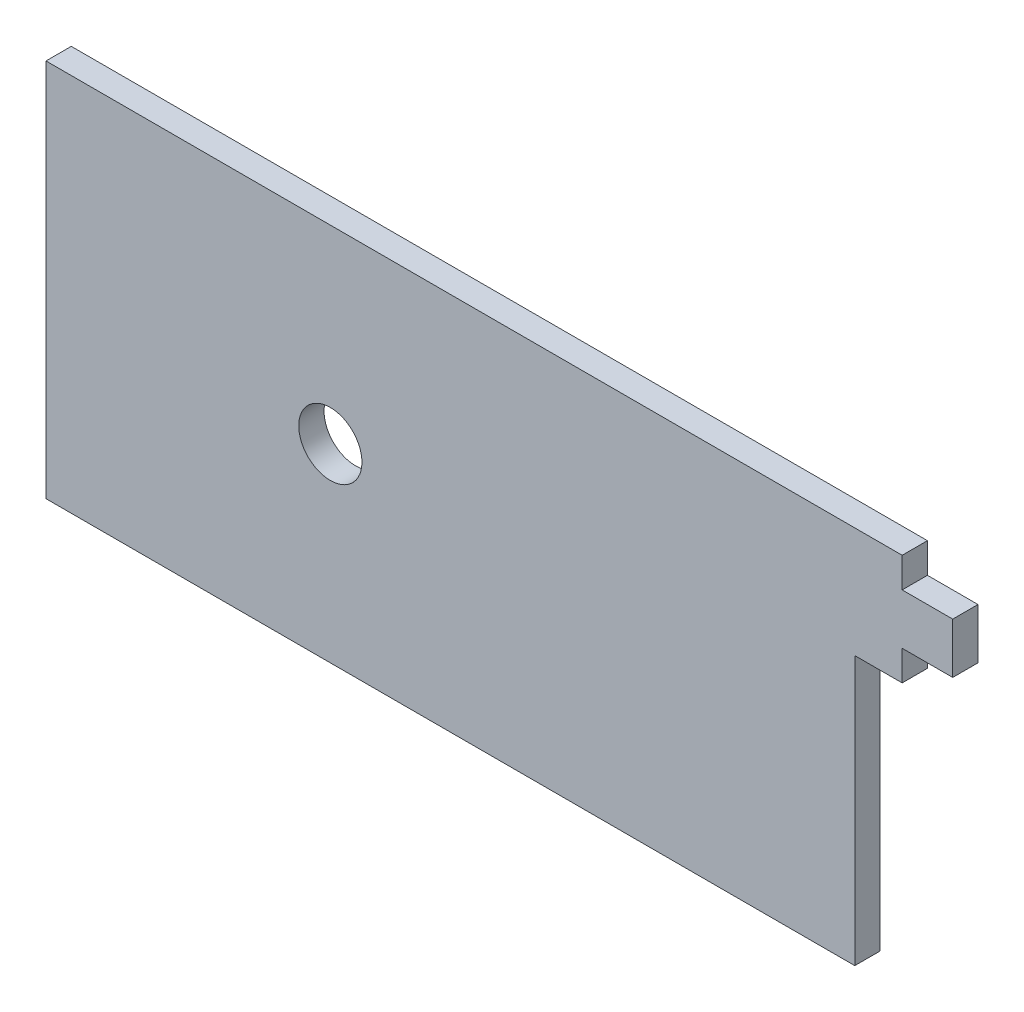
SolidWorks part; units mm, degrees
ref_plane "Front Plane" through (0, 0, 0) normal (0, 0, 1) x (1, 0, 0)
ref_plane "Top Plane" through (0, 0, 0) normal (0, 1, 0) x (1, 0, 0)
ref_plane "Right Plane" through (0, 0, 0) normal (1, 0, 0) x (0, 0, -1)
sketch "Sketch1" plane through (0, 0, 0) normal (0, 0, 1) x (1, 0, 0)
  line L0 (47, 30) -> (54.5, 30)
  line L1 (-81, -30) -> (47, -30)
  line L2 (-81, -30) -> (-81, 30)
  line L3 (-81, 30) -> (47, 30)
  line L4 (47, -30) -> (47, 30) construction
  line L6 (54.5, 12.5) -> (47, 12.5)
  line L11 (54.5, 30) -> (54.5, 12.5) construction
  line L12 (54.5, 30) -> (54.5, 25.25)
  line L13 (47, 12.5) -> (47, -30)
  line L14 (54.5, 25.25) -> (62.5, 25.25)
  line L15 (62.5, 25.25) -> (62.5, 17.25)
  line L16 (62.5, 17.25) -> (54.5, 17.25)
  line L17 (54.5, 17.25) -> (54.5, 12.5)
  circle A4 centre (-36, 0) radius 5
  point P12 (-81, 0)
  point P13 (0, 0)
  dimension "D3" = 17.5
  dimension "D4" = 7.5
  dimension "D5" = 10
  dimension "D1" = 128
  dimension "D6" = 45
  dimension "D2" = 60
  dimension "D7" = 8
  dimension "D8" = 8
extrude "Boss-Extrude1" add sketch "Sketch1" along normal blind 4
